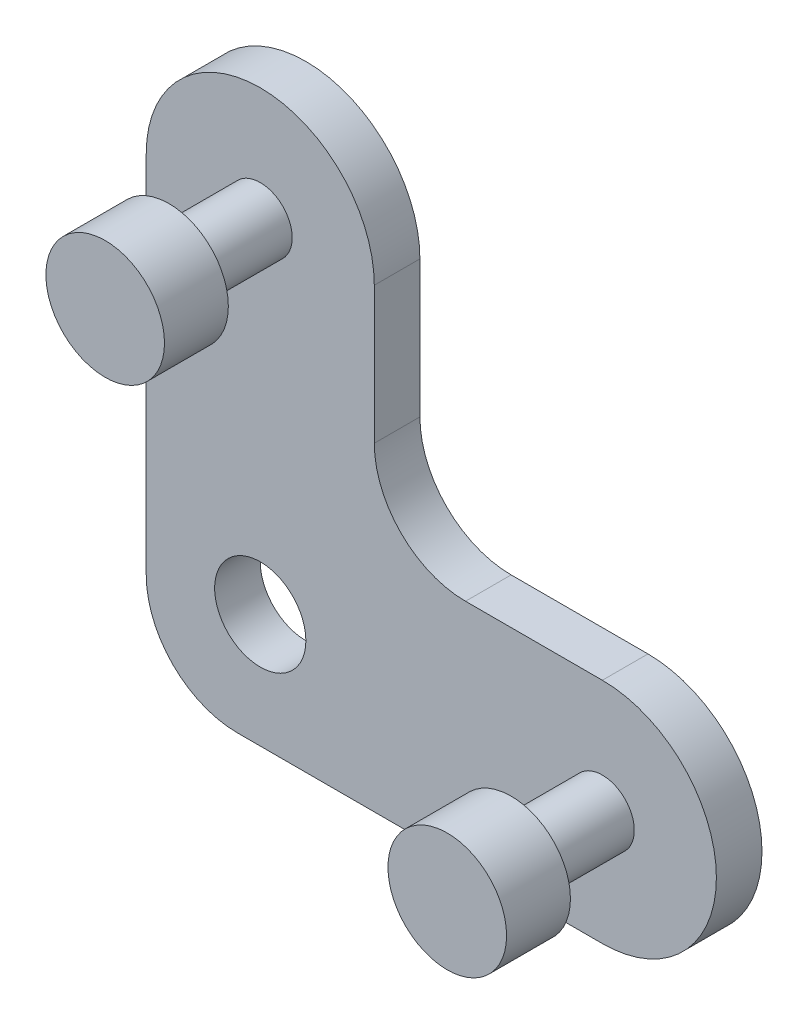
SolidWorks part; units mm, degrees
ref_plane "Front Plane" through (0, 0, 0) normal (0, 0, 1) x (1, 0, 0)
ref_plane "Top Plane" through (0, 0, 0) normal (0, 1, 0) x (1, 0, 0)
ref_plane "Right Plane" through (0, 0, 0) normal (1, 0, 0) x (0, 0, -1)
sketch "Sketch1" plane through (0, 0, 0) normal (0, 0, 1) x (1, 0, 0)
  line L0 (0, 12.7) -> (0, 2.54)
  line L1 (2.54, 0) -> (12.7, 0)
  line L2 (6.35, 12.7) -> (6.35, 8.89)
  line L3 (8.89, 6.35) -> (12.7, 6.35)
  line L4 (0, 12.7) -> (0, 0) construction
  line L5 (0, 0) -> (12.7, 0) construction
  line L6 (6.35, 12.7) -> (6.35, 6.35) construction
  line L7 (6.35, 6.35) -> (12.7, 6.35) construction
  arc A0 (0, 12.7) -> (6.35, 12.7) centre (3.175, 12.7) cw
  arc A1 (12.7, 0) -> (12.7, 6.35) centre (12.7, 3.175) ccw
  arc A2 (0, 2.54) -> (2.54, 0) centre (2.54, 2.54) ccw
  arc A3 (6.35, 8.89) -> (8.89, 6.35) centre (8.89, 8.89) ccw
  point P12 (0, 0)
  point P16 (-26.2469, 14.1001)
  dimension "D4" = 2.54
  dimension "D1" = 12.7
  dimension "D2" = 12.7
  dimension "D3" = 6.35
extrude "body" add sketch "Sketch1" along normal blind 1.27
sketch "Sketch2" plane through (0, 0, 1.27) normal (0, 0, 1) x (1, 0, 0)
  circle A0 centre (3.175, 12.7) radius 0.889
  circle A1 centre (12.7, 3.175) radius 0.889
  dimension "D1" = 1.778
  dimension "D2" = 1.778
extrude "nubs" add sketch "Sketch2" along normal blind 2.54
sketch "Sketch3" plane through (0, 0, 3.81) normal (0, 0, 1) x (1, 0, 0)
  circle A0 centre (12.7, 3.175) radius 1.651
  circle A1 centre (3.175, 12.7) radius 1.651
  dimension "D1" = 3.302
  dimension "D2" = 3.302
extrude "don't let it fall off" add sketch "Sketch3" along normal blind 1.778
sketch "references" plane through (0, 0, 1.27) normal (0, 0, 1) x (1, 0, 0)
  line L0 (38.1, 3.175) -> (-5.5398, 3.175) construction
  line L1 (3.175, 38.1) -> (3.175, -6.489) construction
ref_point "centre of hole"
sketch "Sketch5" plane through (0, 0, 1.27) normal (0, 0, 1) x (1, 0, 0)
  circle A0 centre (3.175, 3.175) radius 1.27
  dimension "D1" = 2.54
extrude "attach to side" cut sketch "Sketch5" against normal up to next
